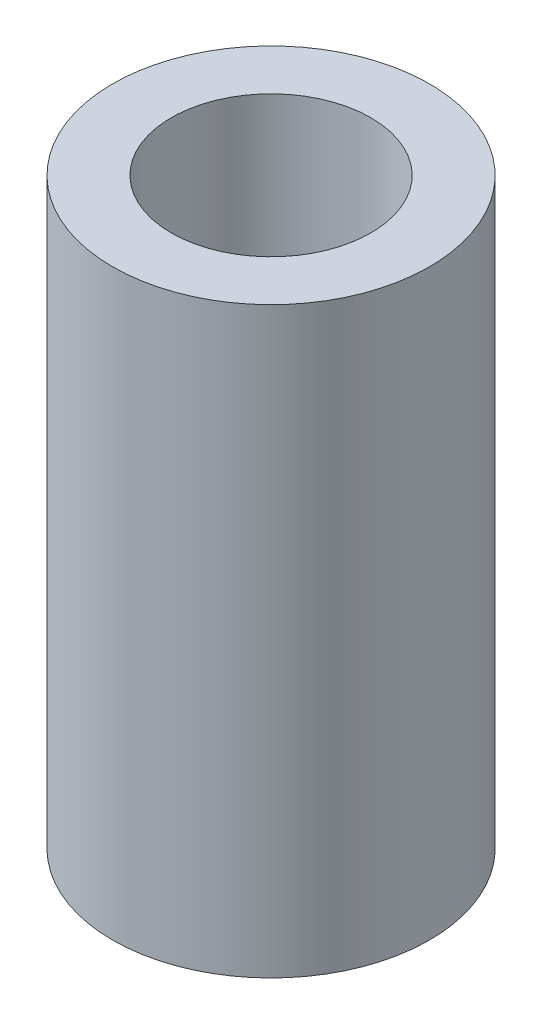
SolidWorks part; units mm, degrees
material "6061-T6 (SS)"
ref_plane "X-Y Datum" through (0, 0, 0) normal (0, 0, 1) x (1, 0, 0)
ref_plane "X-Z Datum" through (0, 0, 0) normal (0, 1, 0) x (1, 0, 0)
ref_plane "Y-Z Datum" through (0, 0, 0) normal (1, 0, 0) x (0, 0, -1)
sketch "Sketch1" plane through (0, 0, 0) normal (0, 1, 0) x (1, 0, 0)
  circle A0 centre (0, 0) radius 3.175
  circle A1 centre (0, 0) radius 2
  dimension "D1" = 6.35
  dimension "D2" = 4
extrude "Boss-Extrude1" add sketch "Sketch1" against normal blind 11.684
